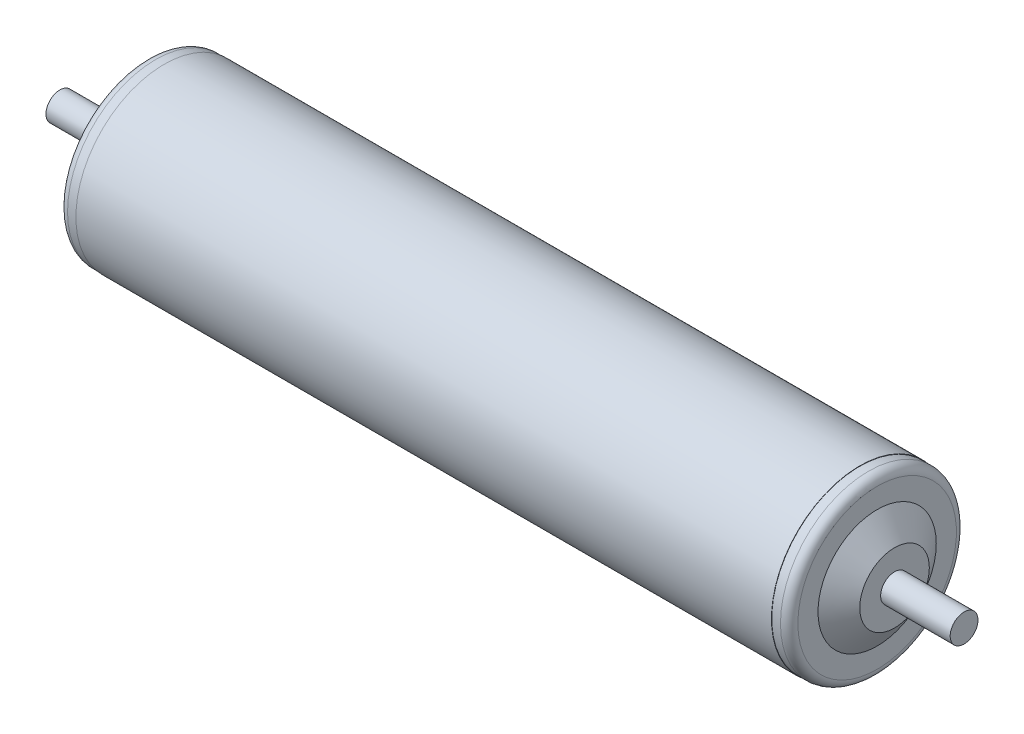
SolidWorks part; units mm, degrees
ref_plane "Front Plane" through (0, 0, 0) normal (0, 0, 1) x (1, 0, 0)
ref_plane "Top Plane" through (0, 0, 0) normal (0, 1, 0) x (1, 0, 0)
ref_plane "Right Plane" through (0, 0, 0) normal (1, 0, 0) x (0, 0, -1)
sketch "Sketch1" plane through (0, 0, 0) normal (0, 1, 0) x (1, 0, 0)
  line L0 (-100, -25.4) -> (100, -25.4)
  line L1 (100, -25.4) -> (100, -25.3)
  line L2 (100, -25.3) -> (105, -25.3)
  line L3 (105, -25.3) -> (105, -17)
  line L4 (105, -17) -> (110, -10)
  line L5 (110, -10) -> (110, -4)
  line L6 (110, -4) -> (130, -4)
  line L7 (130, -4) -> (130, 0)
  line L8 (130, 0) -> (-130, 0)
  line L9 (0, 0) -> (0, -25.4)
  line L10 (-130, -4) -> (-130, 0)
  line L11 (-110, -4) -> (-130, -4)
  line L12 (-110, -10) -> (-110, -4)
  line L13 (-105, -17) -> (-110, -10)
  line L14 (-105, -25.3) -> (-105, -17)
  line L15 (-100, -25.3) -> (-105, -25.3)
  line L16 (-100, -25.4) -> (-100, -25.3)
  dimension "D1" = 100
  dimension "D2" = 5
  dimension "D3" = 130
  dimension "D4" = 110
  dimension "D5" = 4
  dimension "D6" = 25.4
  dimension "D7" = 0.1
  dimension "D8" = 17
  dimension "D9" = 10
revolve "Revolve1" add sketch "Sketch1" angle 360 about L8
fillet "Fillet1" radius 2.5 2 edges at (-105, 0, -25.3) (105, 0, -25.3)
